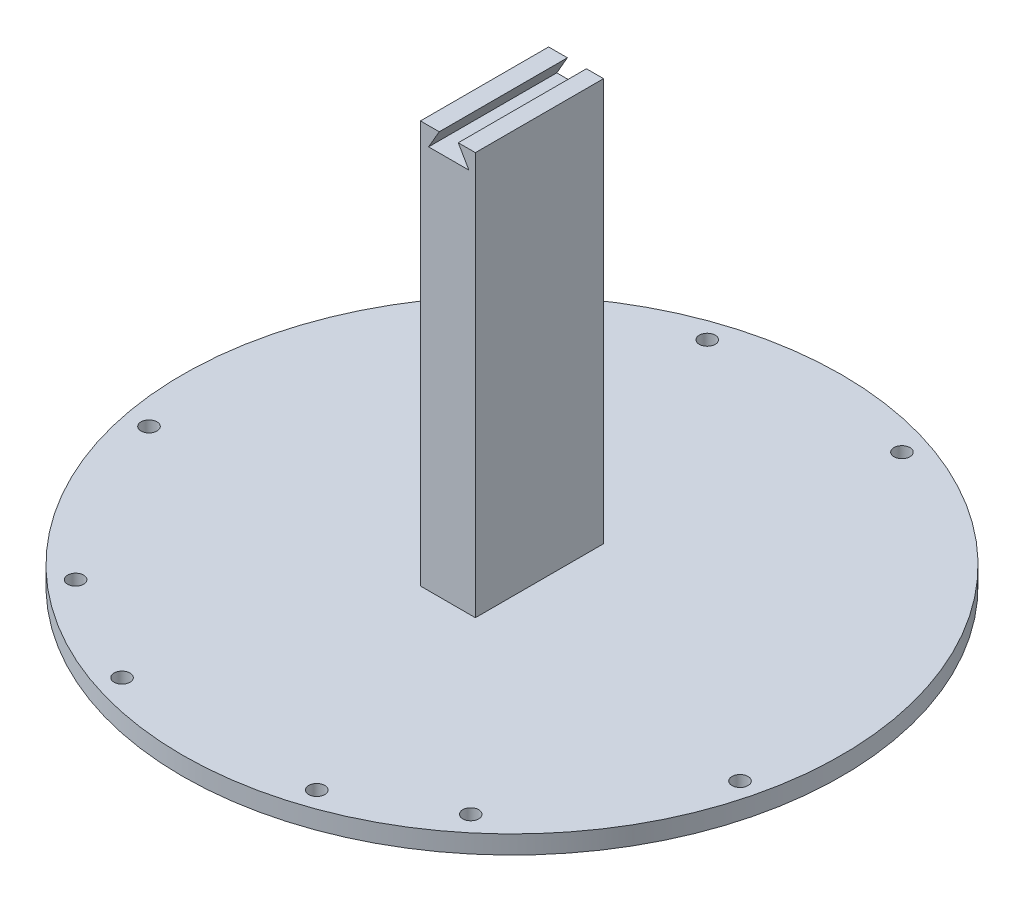
SolidWorks part; units mm, degrees
ref_plane "Front Plane" through (0, 0, 0) normal (0, 0, 1) x (1, 0, 0)
ref_plane "Top Plane" through (0, 0, 0) normal (0, 1, 0) x (1, 0, 0)
ref_plane "Right Plane" through (0, 0, 0) normal (1, 0, 0) x (0, 0, -1)
sketch "Sketch1" plane through (0, 0, 0) normal (0, 1, 0) x (1, 0, 0)
  circle A0 centre (0, 0) radius 90
  dimension "D1" = 180
extrude "Boss-Extrude1" add sketch "Sketch1" along normal blind 5
sketch "Sketch2" plane through (0, 5, 0) normal (0, 1, 0) x (1, 0, 0)
  line L1 (7.5, -17.5) -> (-7.5, -17.5)
  line L2 (7.5, -17.5) -> (7.5, 17.5)
  line L3 (7.5, 17.5) -> (-7.5, 17.5)
  line L4 (-7.5, -17.5) -> (-7.5, 17.5)
  line L5 (7.5, -17.5) -> (-7.5, 17.5) construction
  line L6 (7.5, 17.5) -> (-7.5, -17.5) construction
  point P0 (0, 0)
  dimension "D1" = 35
  dimension "D2" = 15
extrude "Boss-Extrude2" add sketch "Sketch2" along normal blind 110
sketch "Sketch3" plane through (0, 0, 17.5) normal (0, 0, 1) x (1, 0, 0)
  line L0 (-2.3736, 115) -> (2.8264, 115)
  line L1 (-7.5, 115) -> (7.5, 115) construction
  line L2 (5.7264, 109.9771) -> (-5.2736, 109.9771)
  line L3 (-5.2736, 109.9771) -> (-2.3736, 115)
  line L4 (2.8264, 115) -> (5.7264, 109.9771)
  point P5 (0.2264, 115)
  point P8 (0.2264, 109.9771)
  dimension "D1" = 5.2
  dimension "D2" = 11
  dimension "D3" = 60
  dimension "D4" = 5.8
extrude "Cut-Extrude1" cut sketch "Sketch3" against normal blind 36
sketch "Sketch4" plane through (0, 0, 0) normal (0, -1, 0) x (-1, 0, 0)
  line L0 (-82.2453, -19.9781) -> (-53.3466, -64.6125)
  line L1 (56.0932, -63.0822) -> (82.3103, -16.8252)
  line L2 (26.585, -79.9073) -> (-26.585, -79.9073)
  line L3 (26.585, 79.9073) -> (-26.585, 79.9073)
  circle A0 centre (0, 0) radius 79.9073
  arc A1 (-79.9073, 0) -> (-67.7959, -42.2953) centre (0, 0) ccw
  arc A2 (79.9073, 0) -> (69.2018, -39.9537) centre (0, 0) cw
  circle A3 centre (-82.2453, -19.9781) radius 2.1826
  circle A4 centre (-53.3466, -64.6125) radius 2.1826
  circle A5 centre (82.3103, -16.8252) radius 2.1826
  circle A6 centre (56.0932, -63.0822) radius 2.1826
  circle A7 centre (-26.585, -79.9073) radius 2.1826
  circle A8 centre (26.585, -79.9073) radius 2.1826
  circle A9 centre (-26.585, 79.9073) radius 2.1826
  circle A10 centre (26.585, 79.9073) radius 2.1826
  point P10 (-67.7959, -42.2953)
  point P15 (69.2018, -39.9537)
  point P20 (0, -79.9073)
  point P25 (0, 79.9073)
  dimension "D1" = 53.173
  dimension "D2" = 4.3651
  dimension "D3" = 4.3651
  dimension "D5" = 4.3651
  dimension "D6" = 4.3651
  dimension "D7" = 53.17
  dimension "D8" = 4.3651
  dimension "D9" = 4.3651
  dimension "D10" = 4.3651
  dimension "D11" = 4.3651
  dimension "D4" = 53.17
  dimension "D12" = 53.17
extrude "Cut-Extrude2" cut sketch "Sketch4" against normal blind 62
